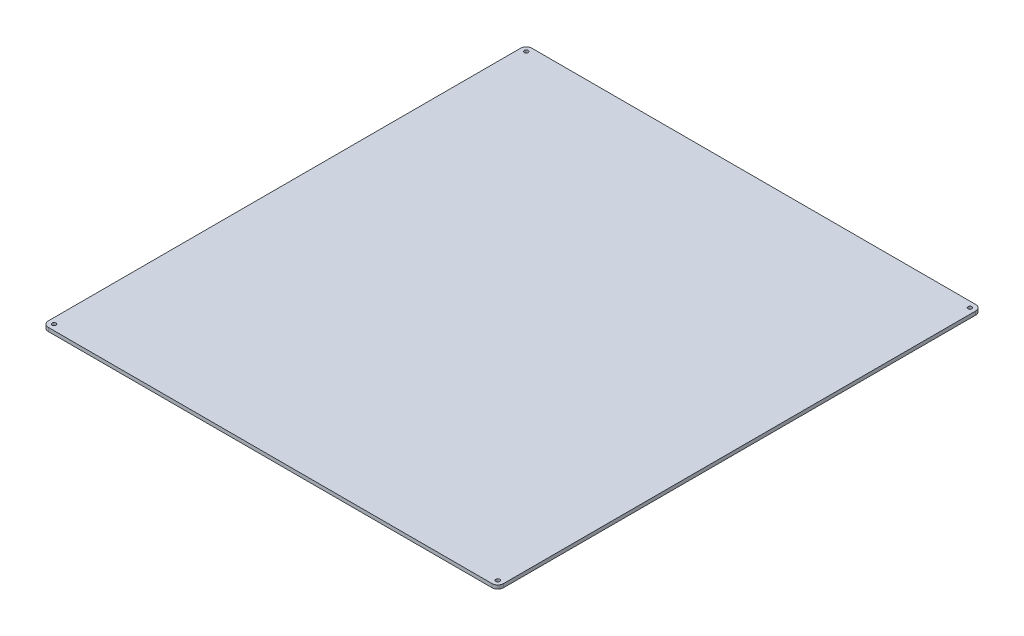
SolidWorks part; units mm, degrees
ref_plane "Front Plane" through (0, 0, 0) normal (0, 0, 1) x (1, 0, 0)
ref_plane "Top Plane" through (0, 0, 0) normal (0, 1, 0) x (1, 0, 0)
ref_plane "Right Plane" through (0, 0, 0) normal (1, 0, 0) x (0, 0, -1)
sketch "Sketch2" plane through (0, 0, 0) normal (0, 1, 0) x (1, 0, 0)
  line L1 (0, 0) -> (400, 0)
  line L2 (0, 0) -> (0, 425)
  line L3 (0, 425) -> (400, 425)
  line L4 (400, 0) -> (400, 425)
  dimension "D1" = 425
  dimension "D2" = 400
extrude "Boss-Extrude1" add sketch "Sketch2" along normal blind 3.175
hole_wizard "M3 Clearance Hole1" positions "3DSketch1" profile "Sketch3" hole size "M3" standard "ISO" end condition through all
sketch3d "3DSketch1"
  line L7 (5, 3.175, -420) -> (0, 3.175, -420) construction
  line L8 (0, 3.175, -425) -> (0, 3.175, 0) construction
  line L10 (5, 3.175, -420) -> (5, 3.175, -425) construction
  line L11 (400, 3.175, -425) -> (0, 3.175, -425) construction
  line L12 (395, 3.175, -425) -> (395, 3.175, -420) construction
  line L13 (395, 3.175, -420) -> (400, 3.175, -420) construction
  line L14 (400, 3.175, 0) -> (400, 3.175, -425) construction
  line L16 (0, 3.175, -5) -> (5, 3.175, -5) construction
  line L17 (5, 3.175, -5) -> (5, 3.175, 0) construction
  line L18 (0, 3.175, 0) -> (400, 3.175, 0) construction
  line L20 (400, 3.175, -5) -> (395, 3.175, -5) construction
  line L21 (395, 3.175, -5) -> (395, 3.175, 0) construction
  point P0 (5, 3.175, -420)
  point P44 (395, 3.175, -420)
  point P46 (5, 3.175, -5)
  point P48 (395, 3.175, -5)
  dimension "D1" = 5
  dimension "D2" = 5
sketch "Sketch3" plane through (5, 3.175, -420) normal (1, 0, 0) x (0, 0, 1)
  line L0 (0, 0) -> (0, 3.175)
  line L1 (0, 3.175) -> (1.7, 3.175)
  line L2 (1.7, 3.175) -> (1.7, 0)
  line L5 (1.7, 0) -> (0, 0)
  line L11 (0, -6.35) -> (0, 107.95) construction
  dimension "Thru Hole Dia." = 3.4
  dimension "Thru Hole Depth" = 3.175
fillet "Fillet1" radius 5 4 edges at (0, 1.5875, 0) (400, 1.5875, 0) (0, 1.5875, -425) (400, 1.5875, -425)
